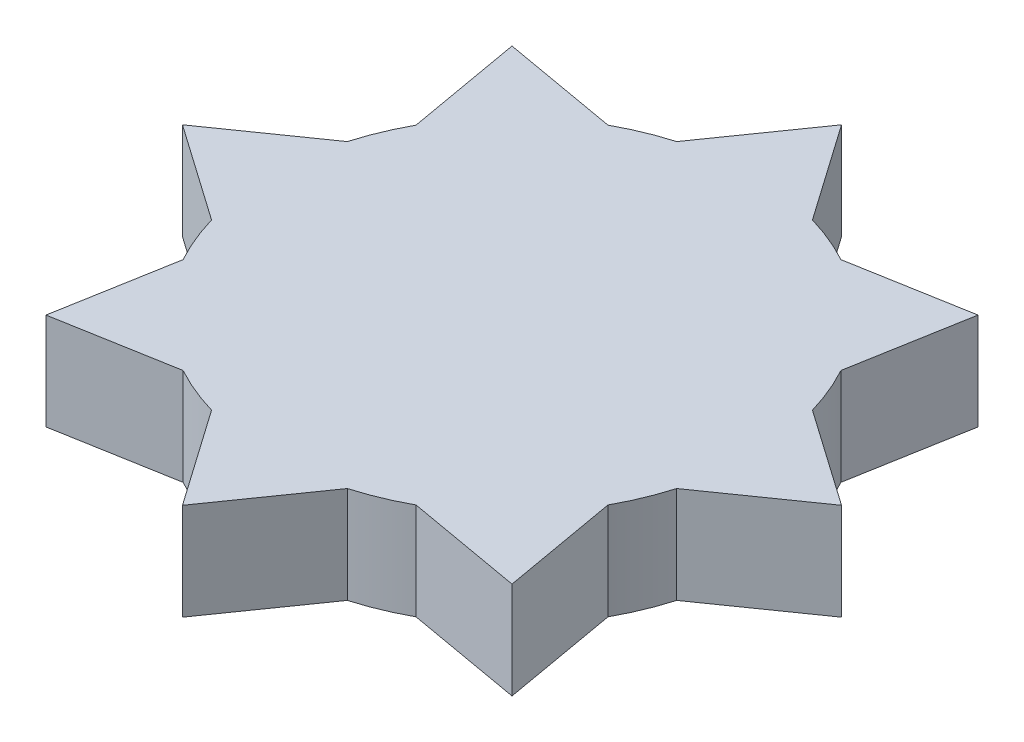
SolidWorks part; units mm, degrees
ref_plane "Front Plane" through (0, 0, 0) normal (0, 0, 1) x (1, 0, 0)
ref_plane "Top Plane" through (0, 0, 0) normal (0, 1, 0) x (1, 0, 0)
ref_plane "Right Plane" through (0, 0, 0) normal (1, 0, 0) x (0, 0, -1)
sketch "Sketch1" plane through (0, 0, 0) normal (0, 1, 0) x (1, 0, 0)
  line L0 (0, 0) -> (0, 40.5981) construction
  line L1 (0, 34) -> (-7.0026, 23.9992)
  line L2 (0, 34) -> (7.0026, 23.9992)
  line L3 (24.0416, 24.0416) -> (12.0184, 21.9216)
  line L4 (24.0416, 24.0416) -> (21.9216, 12.0184)
  line L5 (34, 0) -> (23.9992, 7.0026)
  line L6 (34, 0) -> (23.9992, -7.0026)
  line L7 (24.0416, -24.0416) -> (21.9216, -12.0184)
  line L8 (24.0416, -24.0416) -> (12.0184, -21.9216)
  line L9 (0, -34) -> (7.0026, -23.9992)
  line L10 (0, -34) -> (-7.0026, -23.9992)
  line L11 (-24.0416, -24.0416) -> (-12.0184, -21.9216)
  line L12 (-24.0416, -24.0416) -> (-21.9216, -12.0184)
  line L13 (-34, 0) -> (-23.9992, -7.0026)
  line L14 (-34, 0) -> (-23.9992, 7.0026)
  line L15 (-24.0416, 24.0416) -> (-21.9216, 12.0184)
  line L16 (-24.0416, 24.0416) -> (-12.0184, 21.9216)
  circle A0 centre (0, 0) radius 25
  point P30 (0, 0)
  dimension "D2" = 50
  dimension "D1" = 0
  dimension "D3" = 35
  dimension "D4" = 34
  dimension "D5" = 8
extrude "Boss-Extrude1" add sketch "Sketch1" along normal blind 10
